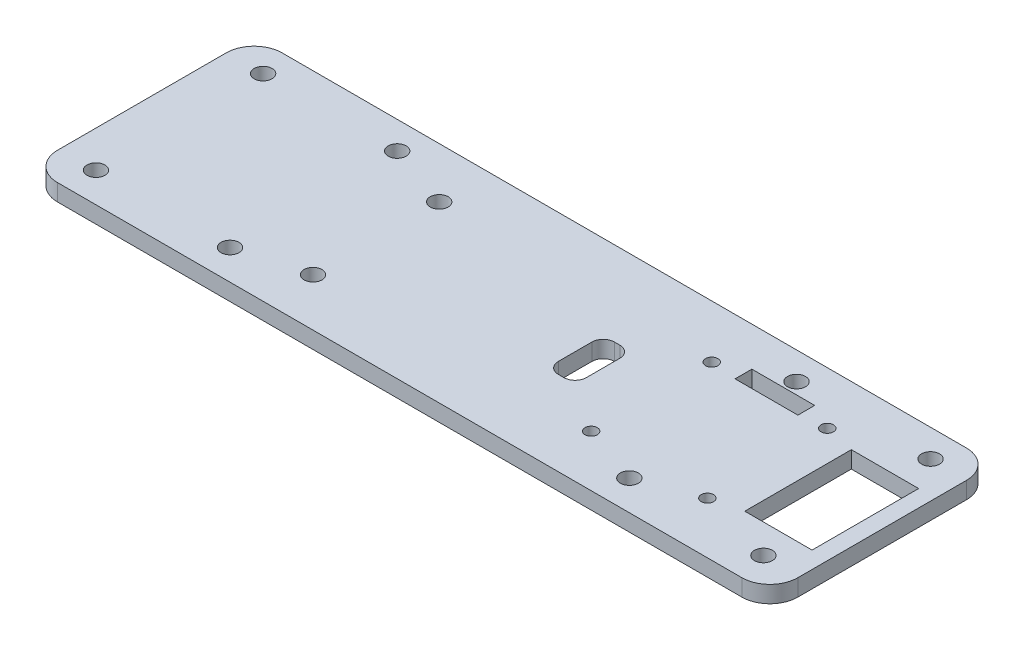
SolidWorks part; units mm, degrees
ref_plane "前视基准面" through (0, 0, 0) normal (0, 0, 1) x (1, 0, 0)
ref_plane "上视基准面" through (0, 0, 0) normal (0, 1, 0) x (1, 0, 0)
ref_plane "右视基准面" through (0, 0, 0) normal (1, 0, 0) x (0, 0, -1)
other "Configuration Table"
sketch "草图1" plane through (0, 0, 0) normal (0, 1, 0) x (1, 0, 0)
  line L0 (-40.8508, 4.523) -> (-40.8508, 14.9172) construction
  line L1 (-106.8508, 24.548) -> (25.1492, 24.548)
  line L2 (-106.8508, 24.548) -> (-106.8508, -15.502)
  line L3 (-106.8508, -15.502) -> (25.1492, -15.502)
  line L4 (25.1492, 24.548) -> (25.1492, -15.502)
  line L5 (-106.8508, 24.548) -> (25.1492, -15.502) construction
  line L6 (-106.8508, -15.502) -> (25.1492, 24.548) construction
  circle A1 centre (18.6492, 19.648) radius 1.6
  circle A2 centre (18.6492, -10.152) radius 1.6
  circle A3 centre (-5.2508, 19.648) radius 1.6
  circle A4 centre (-5.2508, -10.152) radius 1.6
  circle A5 centre (-100.3508, -10.152) radius 1.6
  circle A6 centre (-76.4508, -10.152) radius 1.6
  circle A7 centre (-100.3508, 19.648) radius 1.6
  circle A8 centre (-76.4508, 19.648) radius 1.6
  point P0 (-40.8508, 4.523)
  dimension "D3" = 4.9
  dimension "D4" = 6.5
  dimension "D5" = 29.8
  dimension "D6" = 23.9
  dimension "D1" = 132
  dimension "D2" = 40.05
  dimension "D7" = 29.8
extrude "凸台-拉伸1" add sketch "草图1" along normal blind 3
fillet "圆角1" radius 5 1 edges at (25.1492, 1.5, -24.548)
fillet "圆角2" radius 5 3 edges at (-106.8508, 1.5, -24.548) (-106.8508, 1.5, 15.502) (25.1492, 1.5, 15.502)
ref_plane "基准面1" through (-40.8508, 0, 0) normal (1, 0, 0) x (0, 0, -1)
sketch "草图4" plane through (0, 3, 0) normal (0, 1, 0) x (1, 0, 0)
  line L0 (25.1492, -10.502) -> (25.1492, 19.548) construction
  line L1 (10.1492, 14.023) -> (22.1492, 14.023)
  line L2 (10.1492, 14.023) -> (10.1492, -4.977)
  line L3 (10.1492, -4.977) -> (22.1492, -4.977)
  line L4 (22.1492, 14.023) -> (22.1492, -4.977)
  line L5 (10.1492, 14.023) -> (22.1492, -4.977) construction
  line L6 (10.1492, -4.977) -> (22.1492, 14.023) construction
  line L7 (-40.8508, 4.523) -> (-27.3033, 4.523) construction
  line L8 (-40.8508, -1.65) -> (-40.8508, 1.65) construction
  line L9 (20.1492, 24.548) -> (-101.8508, 24.548) construction
  line L11 (-18.2508, 17.593) -> (7.1492, 17.593) construction
  line L12 (-18.2508, 17.593) -> (-18.2508, -8.547) construction
  line L13 (-18.2508, -8.547) -> (7.1492, -8.547) construction
  line L14 (7.1492, 17.593) -> (7.1492, -8.547) construction
  line L15 (-18.2508, 17.593) -> (7.1492, -8.547) construction
  line L16 (-18.2508, -8.547) -> (7.1492, 17.593) construction
  line L17 (-11.1508, 17.593) -> (0.0492, 17.593)
  line L18 (-11.1508, 17.593) -> (-11.1508, 14.593)
  line L19 (-11.1508, 14.593) -> (0.0492, 14.593)
  line L20 (0.0492, 17.593) -> (0.0492, 14.593)
  line L21 (-11.1508, 17.593) -> (0.0492, 14.593) construction
  line L22 (-11.1508, 14.593) -> (0.0492, 17.593) construction
  circle A0 centre (4.7066, 15.173) radius 1.1
  circle A1 centre (4.7992, -6.297) radius 1.1
  circle A2 centre (-15.8108, 15.093) radius 1.1
  circle A3 centre (-15.9008, -6.317) radius 1.1
  point P0 (16.1492, 4.523)
  point P13 (-5.5508, 4.523)
  point P26 (-5.5508, 16.093)
  dimension "D10" = 2.4426
  dimension "D12" = 2.35
  dimension "D14" = 2.5
  dimension "D16" = 2.23
  dimension "D1" = 12
  dimension "D2" = 19
  dimension "D3" = 3
  dimension "D4" = 20.025
  dimension "D5" = 0
  dimension "D6" = 25.4
  dimension "D7" = 26.14
  dimension "D8" = 0
  dimension "D9" = 3
  dimension "D11" = 2.42
  dimension "D13" = 2.25
  dimension "D15" = 2.44
  dimension "D17" = 2.35
  dimension "D18" = 3
  dimension "D19" = 11.2
  dimension "D20" = 0
  dimension "D21" = 5.6
extrude "切除-拉伸1" cut sketch "草图4" against normal blind 10 contours A1 | A0 | A2 | A3 | L18 L17 L20 L19 | L2 L1 L4 L3
sketch "草图5" plane through (0, 3, 0) normal (0, 1, 0) x (1, 0, 0)
  line L0 (-106.8508, 19.548) -> (-106.8508, -10.502) construction
  line L1 (20.1492, 24.548) -> (-101.8508, 24.548) construction
  line L2 (25.1492, 4.523) -> (11.9711, 4.523) construction
  line L3 (-29.6008, 9.523) -> (-24.6008, 9.523)
  line L4 (-29.6008, 9.523) -> (-29.6008, -0.477)
  line L5 (-29.6008, -0.477) -> (-24.6008, -0.477)
  line L6 (-24.6008, 9.523) -> (-24.6008, -0.477)
  line L7 (-29.6008, 9.523) -> (-24.6008, -0.477) construction
  line L8 (-29.6008, -0.477) -> (-24.6008, 9.523) construction
  line L9 (25.1492, -10.502) -> (25.1492, 19.548) construction
  circle A0 centre (-64.8508, 15.548) radius 1.6
  circle A1 centre (-64.8508, -6.952) radius 1.6
  point P6 (-27.1008, 4.523)
  point P17 (0, 0)
  dimension "D1" = 42
  dimension "D3" = 22.5
  dimension "D2" = 9
  dimension "D4" = 42
  dimension "D5" = 37.75
  dimension "D6" = 0
  dimension "D7" = 5
  dimension "D8" = 10
extrude "切除-拉伸2" cut sketch "草图5" against normal blind 10 contours L4 L3 L6 L5 | A0 | A1
fillet "圆角3" radius 2 4 edges at (-29.6008, 1.5, 0.477) (-24.6008, 1.5, 0.477) (-24.6008, 1.5, -9.523) (-29.6008, 1.5, -9.523)
